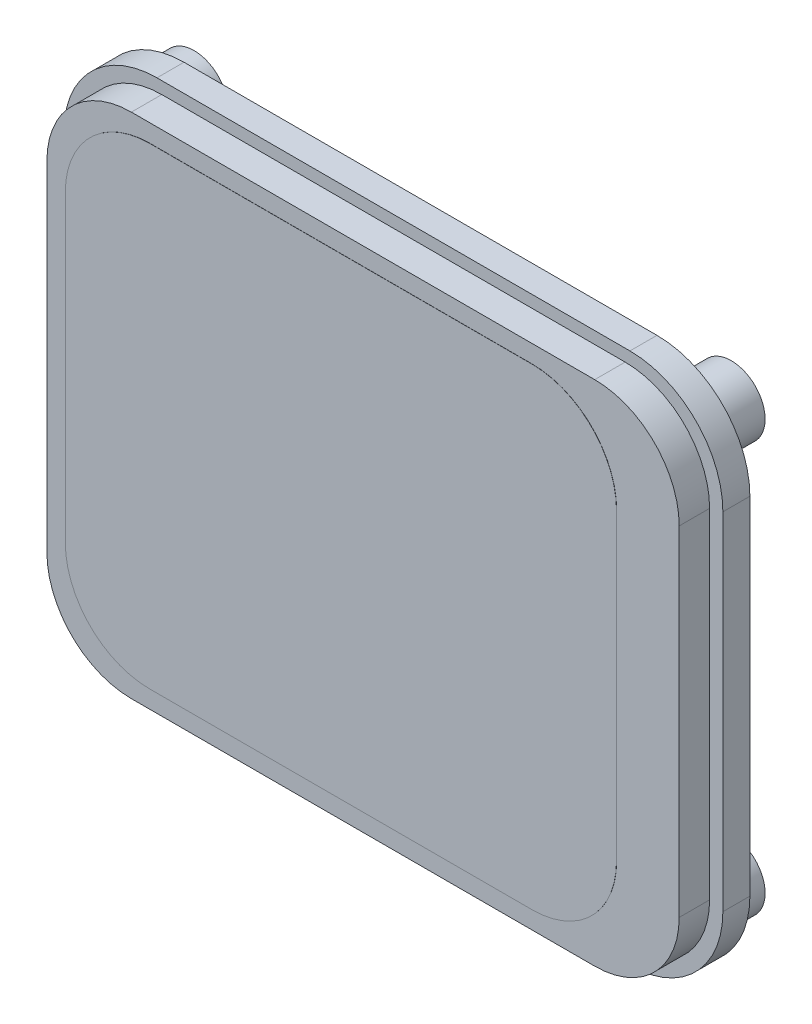
SolidWorks part; units mm, degrees
ref_plane "Plan de face" through (0, 0, 0) normal (0, 0, 1) x (1, 0, 0)
ref_plane "Plan de dessus" through (0, 0, 0) normal (0, 1, 0) x (1, 0, 0)
ref_plane "Plan de droite" through (0, 0, 0) normal (1, 0, 0) x (0, 0, -1)
sketch "Esquisse1" plane through (0, 0, 0) normal (0, 0, 1) x (1, 0, 0)
  line L1 (-11.315, -13.985) -> (11.315, -13.985)
  line L2 (-16.315, -8.985) -> (-16.315, 8.985)
  line L3 (-11.315, 13.985) -> (11.315, 13.985)
  line L4 (16.315, -8.985) -> (16.315, 8.985)
  line L5 (-16.315, -13.985) -> (16.315, 13.985) construction
  line L6 (-16.315, 13.985) -> (16.315, -13.985) construction
  arc A0 (11.315, 13.985) -> (16.315, 8.985) centre (11.315, 8.985) cw
  arc A1 (11.315, -13.985) -> (16.315, -8.985) centre (11.315, -8.985) ccw
  arc A2 (-11.315, -13.985) -> (-16.315, -8.985) centre (-11.315, -8.985) cw
  arc A3 (-16.315, 8.985) -> (-11.315, 13.985) centre (-11.315, 8.985) cw
  point P0 (0, 0)
  dimension "D3" = 5
  dimension "D1" = 32.63
  dimension "D2" = 27.97
extrude "Boss.-Extru.1" add sketch "Esquisse1" against normal blind 0.01
sketch "Esquisse2" plane through (0, 0, -0.01) normal (0, 0, -1) x (-1, 0, 0)
  line L0 (16.315, 8.985) -> (16.315, -8.985) construction
  line L1 (-15.015, -15.035) -> (12.415, -15.035)
  line L2 (-20.015, -10.035) -> (-20.015, 10.035)
  line L3 (-15.015, 15.035) -> (12.415, 15.035)
  line L4 (17.415, -10.035) -> (17.415, 10.035)
  line L5 (-20.015, -15.035) -> (17.415, 15.035) construction
  line L6 (-20.015, 15.035) -> (17.415, -15.035) construction
  arc A0 (12.415, -15.035) -> (17.415, -10.035) centre (12.415, -10.035) ccw
  arc A1 (12.415, 15.035) -> (17.415, 10.035) centre (12.415, 10.035) cw
  arc A2 (-15.015, -15.035) -> (-20.015, -10.035) centre (-15.015, -10.035) cw
  arc A3 (-20.015, 10.035) -> (-15.015, 15.035) centre (-15.015, 10.035) cw
  point P0 (-1.3, 0)
  point P19 (0, 0)
  point P22 (0, 0)
  dimension "D3" = 5
  dimension "D4" = 5
  dimension "D1" = 1.1
  dimension "D2" = 37.43
  dimension "D5" = 30.07
extrude "Boss.-Extru.2" add sketch "Esquisse2" along normal blind 1.8
sketch "Esquisse3" plane through (0, 0, -1.81) normal (0, 0, -1) x (-1, 0, 0)
  line L1 (-15.3, -15.75) -> (12.7, -15.75)
  line L2 (-20.8, -10.25) -> (-20.8, 10.25)
  line L3 (-15.3, 15.75) -> (12.7, 15.75)
  line L4 (18.2, -10.25) -> (18.2, 10.25)
  line L5 (-20.8, -15.75) -> (18.2, 15.75) construction
  line L6 (-20.8, 15.75) -> (18.2, -15.75) construction
  arc A0 (12.7, 15.75) -> (18.2, 10.25) centre (12.7, 10.25) cw
  arc A1 (12.7, -15.75) -> (18.2, -10.25) centre (12.7, -10.25) ccw
  arc A2 (-15.3, -15.75) -> (-20.8, -10.25) centre (-15.3, -10.25) cw
  arc A3 (-20.8, 10.25) -> (-15.3, 15.75) centre (-15.3, 10.25) cw
  point P0 (-1.3, 0)
  dimension "D3" = 5.5
  dimension "D1" = 31.5
  dimension "D2" = 39
extrude "Boss.-Extru.3" add sketch "Esquisse3" along normal blind 1.6
sketch "Esquisse4" plane through (0, 0, -3.41) normal (0, 0, -1) x (-1, 0, 0)
  line L0 (14.6, -12.15) -> (-17.2, -12.15) construction
  line L5 (18.2, -10.25) -> (18.2, 10.25) construction
  line L6 (-15.3, -15.75) -> (12.7, -15.75) construction
  line L7 (0, 0) -> (-6.3271, 0) construction
  circle A4 centre (-17.2, -12.15) radius 2
  circle A5 centre (14.6, -12.15) radius 2
  circle A6 centre (-17.2, 12.15) radius 2
  circle A7 centre (14.6, 12.15) radius 2
  circle A8 centre (-17.2, 12.15) radius 1
  circle A9 centre (-17.2, -12.15) radius 1
  circle A10 centre (14.6, -12.15) radius 1
  circle A11 centre (14.6, 12.15) radius 1
  dimension "D1" = 3.6
  dimension "D4" = 4
  dimension "D5" = 2
  dimension "D2" = 3.6
  dimension "D3" = 31.8
extrude "Boss.-Extru.4" add sketch "Esquisse4" along normal blind 2.5
